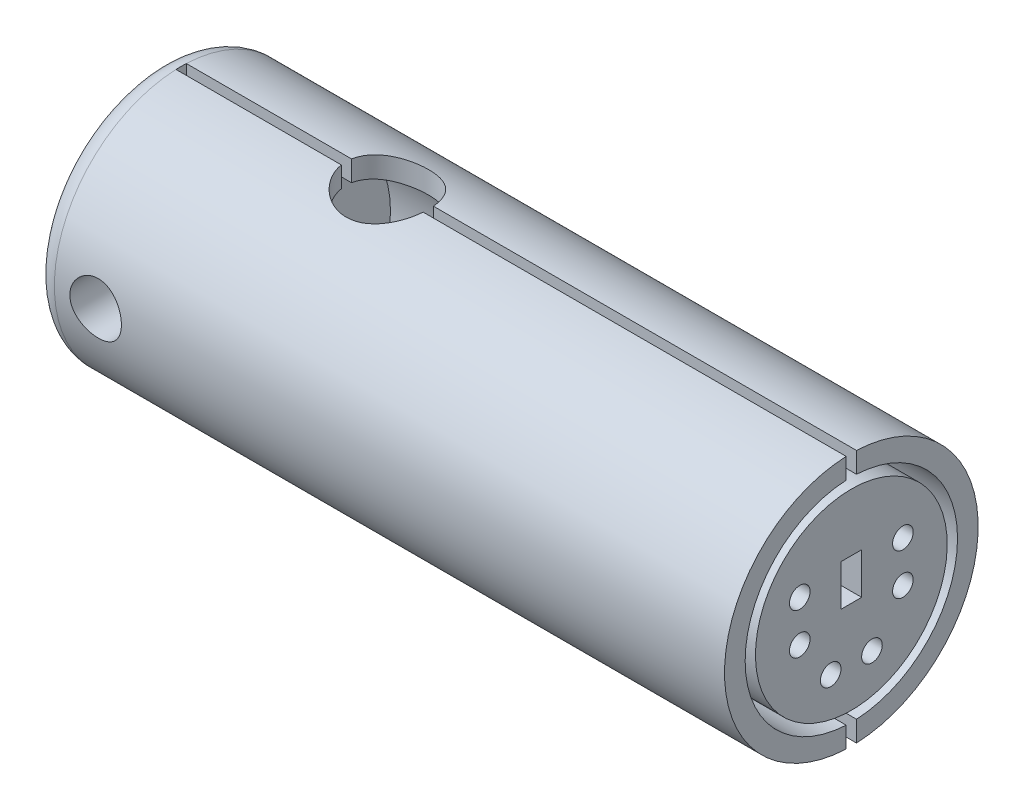
SolidWorks part; units mm, degrees
ref_plane "Спереди" through (0, 0, 0) normal (0, 0, 1) x (1, 0, 0)
ref_plane "Сверху" through (0, 0, 0) normal (0, 1, 0) x (1, 0, 0)
ref_plane "Справа" through (0, 0, 0) normal (1, 0, 0) x (0, 0, -1)
sketch "Эскиз1" plane through (0, 0, 0) normal (0, 0, 1) x (1, 0, 0)
  line L0 (0, 0) -> (0, 6.15)
  line L1 (0, 0) -> (33.5, 0) construction
  line L2 (0, 6.15) -> (33.5, 6.15)
  line L3 (33.5, 0) -> (33.5, 6.15)
  line L4 (0, 0) -> (33.5, 0)
  dimension "D1" = 6.15
  dimension "D2" = 33.5
revolve "Повернуть1" add sketch "Эскиз1" angle 360 about L1
sketch "Эскиз2" plane through (33.5, 0, 0) normal (1, 0, 0) x (0, 0, -1)
  circle A0 centre (0, 0) radius 5.15
  circle A1 centre (0, 0) radius 6.15 construction
  dimension "D1" = 1
extrude "Вырез-Вытянуть1" cut sketch "Эскиз2" against normal blind 27.5
sketch "Эскиз3" plane through (0, 0, 0) normal (-1, 0, 0) x (0, 0, 1)
  circle A0 centre (0, 0) radius 2.25
  dimension "D1" = 4.5
extrude "Вырез-Вытянуть2" cut sketch "Эскиз3" against normal through all
sketch "Эскиз4" plane through (0, 0, 0) normal (-1, 0, 0) x (0, 0, 1)
  line L0 (0, 0) -> (0, 6.15) construction
  line L1 (0, 0) -> (6.15, 0) construction
  circle A0 centre (0, 0) radius 6.15 construction
ref_plane "Плоскость1" through (0, 0, 0) normal (0, 0, 1) x (0, 1, 0)
ref_axis "Ось1" through (6, 0, 0) along (1, 0, 0)
sketch "Эскиз5" plane through (0, 0, 0) normal (0, 0, 1) x (0, 1, 0)
  line L0 (2.25, 0) -> (-2.25, 0) construction
  line L1 (2.25, 0) -> (-2.25, 0) construction
  line L2 (-2.25, -1) -> (-2.25, -5)
  line L3 (-2.25, -1) -> (-3, -1)
  line L4 (-2.25, -5) -> (-3, -5)
  line L5 (-3, -1) -> (-3, -5)
  line L6 (-2.25, -6) -> (2.25, -6) construction
  line L7 (-2.25, -6) -> (2.25, -6) construction
  line L8 (-2.25, 0) -> (-2.25, -6) construction
  dimension "D1" = 1
  dimension "D2" = 1
  dimension "D3" = 0.75
revolve "Вырез-Повернуть1" cut sketch "Эскиз5" angle 360 about axis through (6, 0, 0) along (1, 0, 0)
sketch "Эскиз6" plane through (0, 0, 0) normal (0, 0, 1) x (0, 1, 0)
  line L0 (-3, -1) -> (3, -1) construction
  line L1 (-3, -1) -> (3, -1) construction
  line L2 (3, -5) -> (-3, -5) construction
  line L3 (3, -5) -> (-3, -5) construction
  line L4 (0, -1) -> (0, -5) construction
  circle A0 centre (0, -3) radius 1.25
  dimension "D1" = 2.5
extrude "Вырез-Вытянуть3" cut sketch "Эскиз6" against normal through all and the other way through all
ref_plane "Плоскость2" through (0, 0, 0) normal (0, -1, 0) x (0, 0, 1)
sketch "Эскиз7" plane through (0, 0, 0) normal (0, -1, 0) x (0, 0, 1)
  line L0 (-5.15, -6) -> (5.15, -6) construction
  line L1 (-5.15, -6) -> (5.15, -6) construction
  line L2 (0, -6) -> (0, -11) construction
  circle A0 centre (0, -11) radius 2
  dimension "D1" = 4
  dimension "D2" = 5
extrude "Вырез-Вытянуть4" cut sketch "Эскиз7" against normal through all
fillet "Скругление1" radius 1 1 edges at (0, -6.15, 0)
ref_plane "Плоскость3" through (1, 0, 0) normal (1, 0, 0) x (0, 0, -1)
sketch "Эскиз8" plane through (33.5, 0, 0) normal (1, 0, 0) x (0, 0, -1)
  line L0 (0, 0) -> (0, -6.15) construction
  line L1 (0.25, -6.15) -> (-0.25, -6.15)
  line L2 (0.25, -6.15) -> (0.25, 6.15)
  line L3 (-0.25, -6.15) -> (-0.25, 6.15)
  line L4 (0.25, 6.15) -> (-0.25, 6.15)
  line L5 (0, -6.15) -> (0, 6.15) construction
  circle A0 centre (0, 0) radius 6.15 construction
  dimension "D1" = 0.5
extrude "Вырез-Вытянуть5" cut sketch "Эскиз8" against normal up to surface (32.5 mm away)
sketch "Эскиз9" plane through (33.5, 0, 0) normal (1, 0, 0) x (0, 0, -1)
  line L0 (0, -4.65) -> (0, 4.65) construction
  line L1 (-3.821, -2.65) -> (3.821, -2.65) construction
  line L2 (1, -4.5412) -> (1, 4.5412) construction
  line L3 (2.5, -2.65) -> (2.5, 3.9208) construction
  line L4 (-0.5, 1.85) -> (0.5, 1.85)
  line L5 (-0.5, 1.85) -> (-0.5, -0.15)
  line L6 (0.5, 1.85) -> (0.5, -0.15)
  line L7 (-0.5, -0.15) -> (0.5, -0.15)
  circle A0 centre (0, 0) radius 4.65
  arc A1 (-0.25, 5.1439) -> (-0.25, -5.1439) centre (0, 0) ccw construction
  circle A2 centre (1, -2.65) radius 0.5
  circle A3 centre (2.5, -0.65) radius 0.5
  circle A4 centre (2.5, 1.35) radius 0.5
  circle A5 centre (-2.5, 1.35) radius 0.5
  circle A6 centre (-2.5, -0.65) radius 0.5
  circle A7 centre (-1, -2.65) radius 0.5
  arc A8 (0.25, -5.1439) -> (0.25, 5.1439) centre (0, 0) ccw construction
  circle A9 centre (0, 0) radius 5.15 construction
  point P26 (0, 1.85)
  dimension "D1" = 0.5
  dimension "D4" = 1
  dimension "D6" = 2
  dimension "D2" = 2
  dimension "D3" = 1
  dimension "D5" = 2
  dimension "D7" = 1.5
  dimension "D8" = 1
  dimension "D9" = 2
  dimension "D10" = 2.5
extrude "Бобышка-Вытянуть1" add sketch "Эскиз9" against normal blind 12 separate body
sketch "Эскиз10" plane through (0, 0, 0) normal (0, 0, 1) x (0, 1, 0)
  line L0 (-4.65, -33.5) -> (4.65, -33.5) construction
  line L1 (-4.65, -33.5) -> (4.65, -33.5) construction
  line L2 (4.65, -21.5) -> (-4.65, -21.5) construction
  line L3 (4.65, -21.5) -> (-4.65, -21.5)
  line L4 (0, -33.5) -> (0, -21.5) construction
  circle A0 centre (0, -27.5) radius 1.5
  dimension "D1" = 3
extrude "Бобышка-Вытянуть2" add sketch "Эскиз10" along normal up to surface and the other way up to surface contours A0
